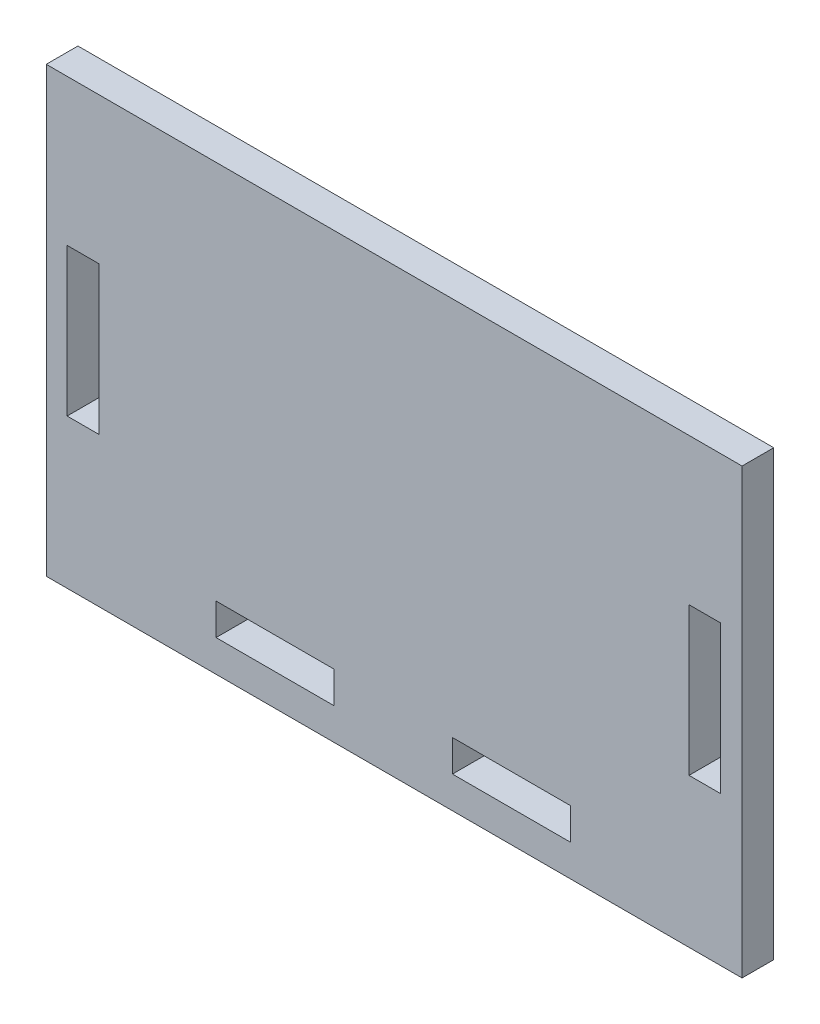
SolidWorks part; units mm, degrees
ref_plane "Plan de face" through (0, 0, 0) normal (0, 0, 1) x (1, 0, 0)
ref_plane "Plan de dessus" through (0, 0, 0) normal (0, 1, 0) x (1, 0, 0)
ref_plane "Plan de droite" through (0, 0, 0) normal (1, 0, 0) x (0, 0, -1)
sketch "Esquisse1" plane through (0, 0, 0) normal (0, 0, 1) x (1, 0, 0)
  line L1 (0.2538, 41.7682) -> (66.1638, 41.7682)
  line L2 (0.2538, 41.7682) -> (0.2538, -0.2318)
  line L3 (0.2538, -0.2318) -> (66.1638, -0.2318)
  line L4 (66.1638, 41.7682) -> (66.1638, -0.2318)
  line L48 (2.2311, 27.9015) -> (5.2311, 27.9015)
  line L49 (2.2311, 27.9015) -> (2.2311, 13.9015)
  line L50 (2.2311, 13.9015) -> (5.2311, 13.9015)
  line L51 (49.9326, 2.7798) -> (38.7309, 2.7798)
  line L52 (49.9326, 2.7798) -> (49.9326, 5.7798)
  line L53 (49.9326, 5.7798) -> (38.7309, 5.7798)
  line L54 (38.7309, 2.7798) -> (38.7309, 5.7798)
  line L55 (27.5326, 2.7798) -> (16.3375, 2.7798)
  line L56 (27.5326, 2.7798) -> (27.5326, 5.7798)
  line L57 (27.5326, 5.7798) -> (16.3375, 5.7798)
  line L58 (16.3375, 2.7798) -> (16.3375, 5.7798)
  line L59 (5.2311, 27.9015) -> (5.2311, 13.9015)
  line L64 (64.1411, 27.8774) -> (61.1366, 27.8774)
  line L65 (64.1411, 27.8774) -> (64.1411, 13.8774)
  line L66 (64.1411, 13.8774) -> (61.1366, 13.8774)
  line L67 (61.1366, 27.8774) -> (61.1366, 13.8774)
  dimension "D1" = 65.91
  dimension "D2" = 42
  dimension "D3" = 3.0045
  dimension "D4" = 14
  dimension "D6" = 11.195
  dimension "D8" = 11.2017
  dimension "D9" = 3
  dimension "D10" = 3
extrude "Boss.-Extru.6" add sketch "Esquisse1" along normal blind 3
sketch "Esquisse6" plane through (0, 0, 3) normal (0, 0, 1) x (1, 0, 0)
